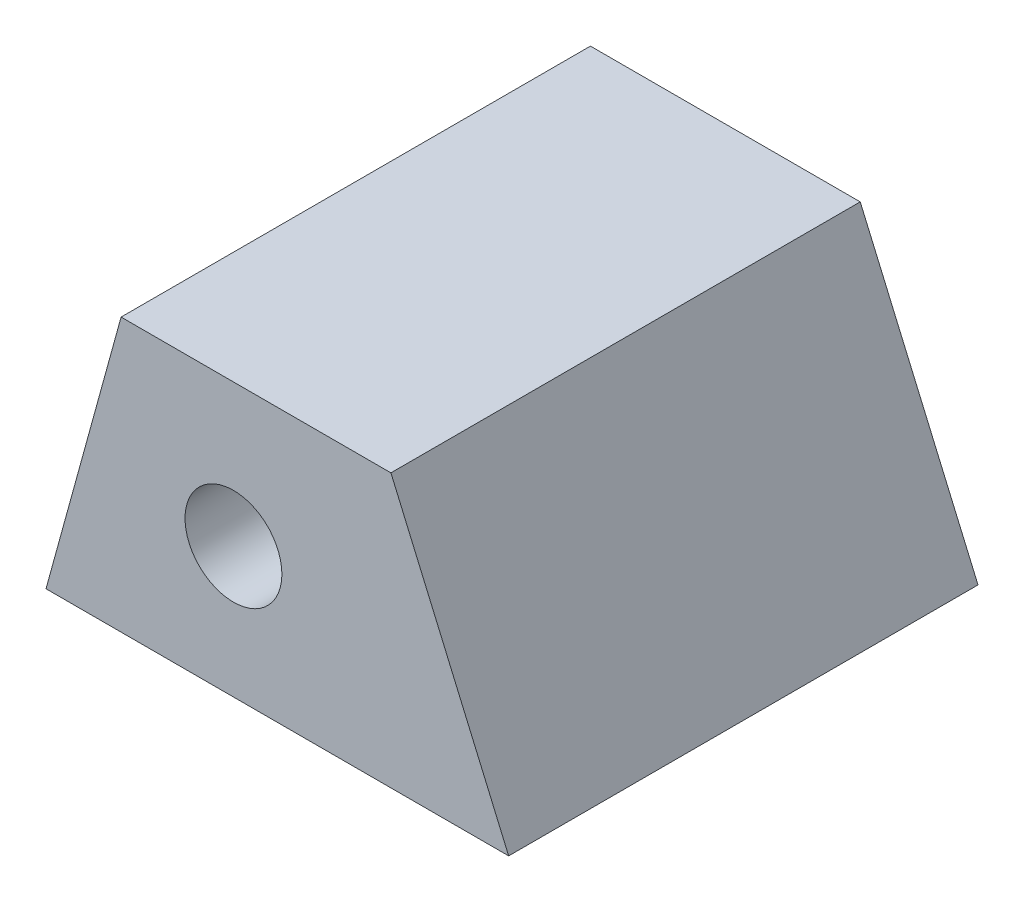
SolidWorks part; units mm, degrees
ref_plane "Спереди" through (0, 0, 0) normal (0, 0, 1) x (1, 0, 0)
ref_plane "Сверху" through (0, 0, 0) normal (0, 1, 0) x (1, 0, 0)
ref_plane "Справа" through (0, 0, 0) normal (1, 0, 0) x (0, 0, -1)
sketch "Sketch1" plane through (0, 0, 0) normal (0, 0, 1) x (1, 0, 0)
  line L0 (0, 0) -> (3.2001, 11.628)
  line L1 (3.2001, 11.628) -> (14.6976, 11.628)
  line L2 (14.6976, 11.628) -> (19.7161, 0)
  line L3 (19.7161, 0) -> (0, 0)
extrude "Boss-Extrude1" add sketch "Sketch1" along normal blind 20
sketch "Sketch2" plane through (0, 0, 20) normal (0, 0, 1) x (1, 0, 0)
  circle A0 centre (7.9882, 5.5641) radius 2.0642
extrude "Cut-Extrude1" cut sketch "Sketch2" against normal blind 29
